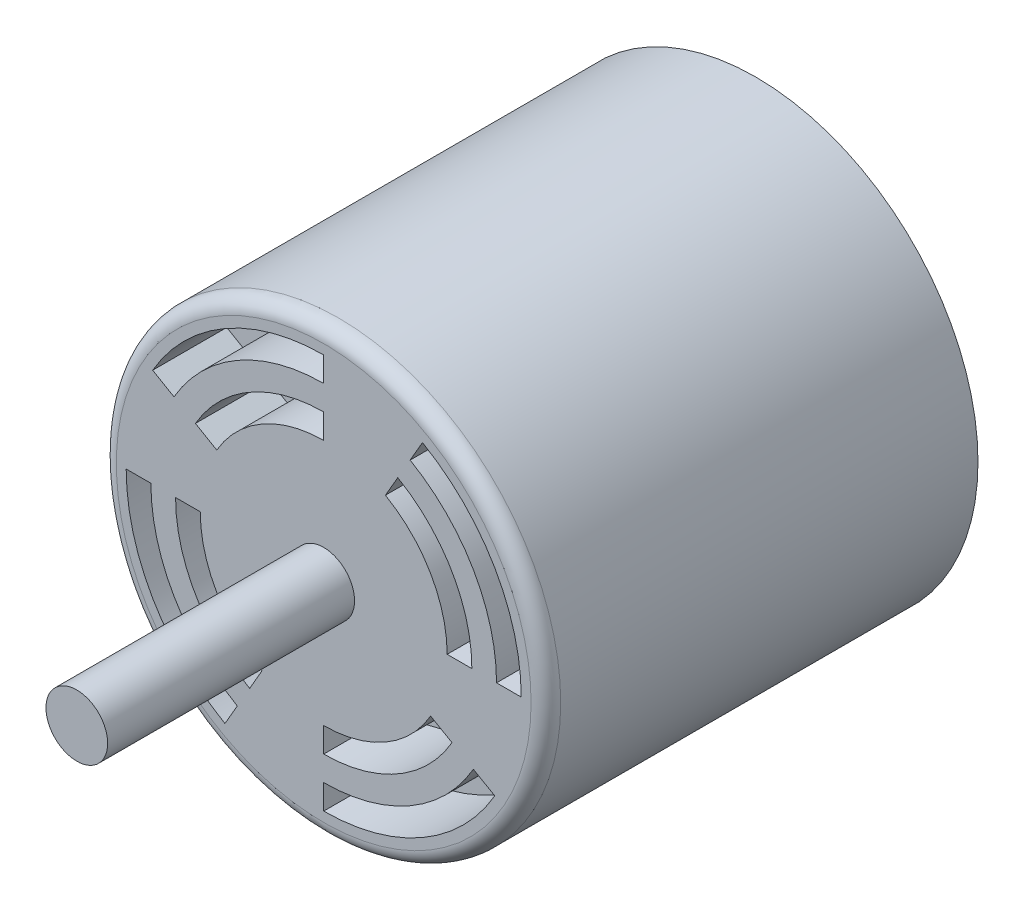
SolidWorks part; units mm, degrees
ref_plane "Front Plane" through (0, 0, 0) normal (0, 0, 1) x (1, 0, 0)
ref_plane "Top Plane" through (0, 0, 0) normal (0, 1, 0) x (1, 0, 0)
ref_plane "Right Plane" through (0, 0, 0) normal (1, 0, 0) x (0, 0, -1)
sketch "Sketch1" plane through (0, 0, 0) normal (0, 0, 1) x (1, 0, 0)
  circle A0 centre (0, 0) radius 22.86
  dimension "D1" = 45.72
extrude "Boss-Extrude1" add sketch "Sketch1" along normal blind 44.45
sketch "Sketch2" plane through (0, 0, 44.45) normal (0, 0, 1) x (1, 0, 0)
  circle A0 centre (0, 0) radius 3.175
  dimension "D1" = 6.35
extrude "Boss-Extrude2" add sketch "Sketch2" along normal blind 25.4
sketch "Sketch3" plane through (0, 0, 44.45) normal (0, 0, 1) x (1, 0, 0)
  line L0 (12.7, 0) -> (15.24, 0)
  line L1 (6.35, 10.9985) -> (7.62, 13.1982)
  line L2 (8.89, 15.3979) -> (10.16, 17.5976)
  line L3 (17.78, 0) -> (20.32, 0)
  line L4 (10.9985, -6.35) -> (13.1982, -7.62)
  line L5 (15.3979, -8.89) -> (17.5976, -10.16)
  line L6 (0, -17.78) -> (0, -20.32)
  line L7 (0, -12.7) -> (0, -15.24)
  line L8 (-6.35, -10.9985) -> (-7.62, -13.1982)
  line L9 (-8.89, -15.3979) -> (-10.16, -17.5976)
  line L10 (-17.78, 0) -> (-20.32, 0)
  line L11 (-12.7, 0) -> (-15.24, 0)
  line L12 (-10.9985, 6.35) -> (-13.1982, 7.62)
  line L13 (-15.3979, 8.89) -> (-17.5976, 10.16)
  line L14 (0, 17.78) -> (0, 20.32)
  line L15 (0, 12.7) -> (0, 15.24)
  arc A0 (12.7, 0) -> (6.35, 10.9985) centre (0, 0) ccw
  arc A1 (15.24, 0) -> (7.62, 13.1982) centre (0, 0) ccw
  arc A2 (20.32, 0) -> (10.16, 17.5976) centre (0, 0) ccw
  arc A3 (17.78, 0) -> (8.89, 15.3979) centre (0, 0) ccw
  arc A4 (0, -15.24) -> (13.1982, -7.62) centre (0, 0) ccw
  circle A5 centre (0, 0) radius 20.32 construction
  circle A6 centre (0, 0) radius 17.78 construction
  circle A7 centre (0, 0) radius 15.24 construction
  circle A8 centre (0, 0) radius 12.7 construction
  arc A9 (0, -12.7) -> (10.9985, -6.35) centre (0, 0) ccw
  arc A10 (0, -17.78) -> (15.3979, -8.89) centre (0, 0) ccw
  arc A11 (0, -20.32) -> (17.5976, -10.16) centre (0, 0) ccw
  arc A12 (-15.24, 0) -> (-7.62, -13.1982) centre (0, 0) ccw
  arc A13 (-12.7, 0) -> (-6.35, -10.9985) centre (0, 0) ccw
  arc A14 (-17.78, 0) -> (-8.89, -15.3979) centre (0, 0) ccw
  arc A15 (-20.32, 0) -> (-10.16, -17.5976) centre (0, 0) ccw
  arc A16 (0, 15.24) -> (-13.1982, 7.62) centre (0, 0) ccw
  arc A17 (0, 12.7) -> (-10.9985, 6.35) centre (0, 0) ccw
  arc A18 (0, 17.78) -> (-15.3979, 8.89) centre (0, 0) ccw
  arc A19 (0, 20.32) -> (-17.5976, 10.16) centre (0, 0) ccw
  point P9 (20.32, 0)
  point P10 (17.78, 0)
  point P15 (15.24, 0)
  point P18 (12.1451, 3.7131)
  dimension "D1" = 25.4
  dimension "D5" = 60
  dimension "D2" = 2.54
  dimension "D3" = 7.62
  dimension "D4" = 5.08
  dimension "D6" = 4
extrude "Cut-Extrude1" cut sketch "Sketch3" against normal blind 7.62
fillet "Fillet1" radius 1.524 1 edges at (22.86, 0, 44.45)
